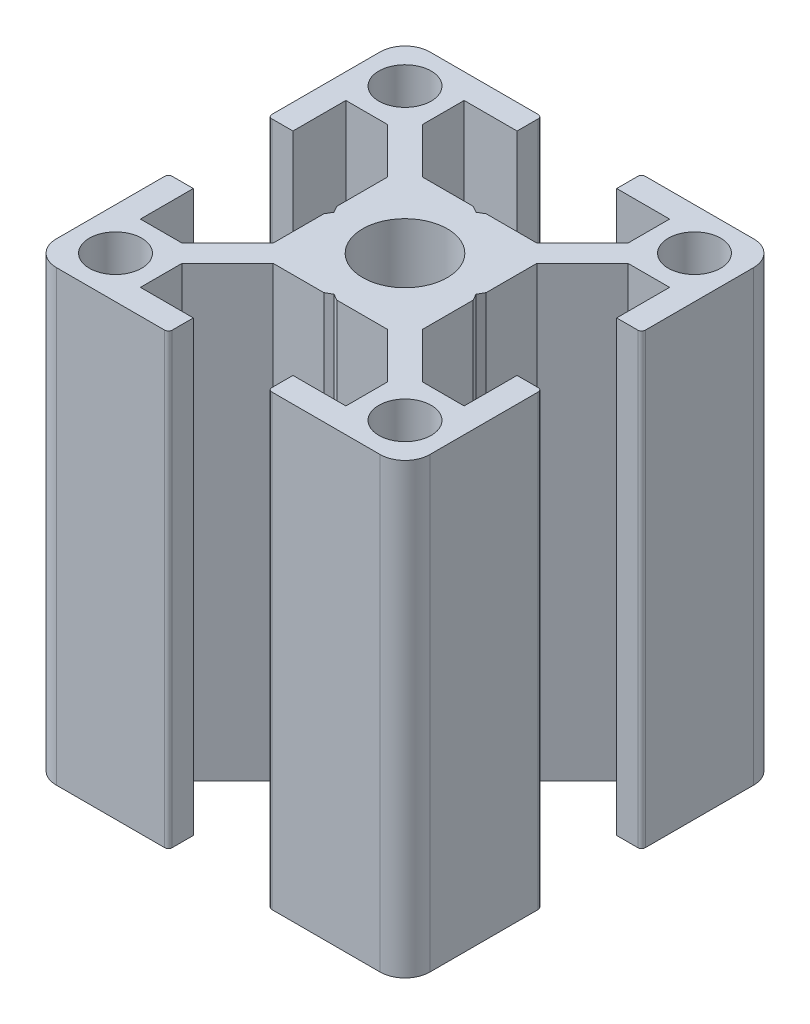
SolidWorks part; units mm, degrees
ref_plane "Front Plane" through (0, 0, 0) normal (0, 0, 1) x (1, 0, 0)
ref_plane "Top Plane" through (0, 0, 0) normal (0, 1, 0) x (1, 0, 0)
ref_plane "Right Plane" through (0, 0, 0) normal (1, 0, 0) x (0, 0, -1)
sketch "Sketch1" plane through (0, 0, 0) normal (0, 0, 1) x (1, 0, 0)
  line L0 (0, 0) -> (0, 36)
  dimension "D1" = 36
ref_plane "Plane1" through (0, 0, 0) normal (0, 1, 0) x (-1, 0, 0)
ref_plane "Plane2" through (0, 0, 0) normal (0, 1, 0) x (-1, 0, 0)
ref_plane "Plane3" through (0, 0, 0) normal (0, 1, 0) x (-1, 0, 0)
ref_plane "Plane4" through (0, 0, 0) normal (0, 1, 0) x (-1, 0, 0)
ref_plane "Plane6" through (0, 0, 0) normal (0, 1, 0) x (-1, 0, 0)
ref_plane "Plane7" through (0, 0, 0) normal (0, 1, 0) x (-1, 0, 0)
other "Structural Member1"
ref_plane "Plane8" through (0, 0, 0) normal (0, 1, 0) x (-1, 0, 0)
sketch "Model" plane through (0, 0, 0) normal (0, 1, 0) x (-1, 0, 0)
  line L0 (-15, 13) -> (-15, 4.3)
  line L1 (-4.3, 15) -> (-13, 15)
  line L2 (-4, 13) -> (-4, 14.7)
  line L3 (-8.25, 13) -> (-4, 13)
  line L4 (-8.25, 9.6642) -> (-8.25, 13)
  line L5 (-4.5858, 6) -> (-8.25, 9.6642)
  line L6 (-0.5196, 6) -> (-4.5858, 6)
  line L7 (0, 5.7) -> (-0.5196, 6)
  line L8 (0.5196, 6) -> (0, 5.7)
  line L9 (4.5858, 6) -> (0.5196, 6)
  line L10 (8.25, 9.6642) -> (4.5858, 6)
  line L11 (8.25, 13) -> (8.25, 9.6642)
  line L12 (4, 13) -> (8.25, 13)
  line L13 (4, 14.7) -> (4, 13)
  line L14 (13, 15) -> (4.3, 15)
  line L15 (15, 4.3) -> (15, 13)
  line L16 (13, 4) -> (14.7, 4)
  line L17 (13, 8.25) -> (13, 4)
  line L18 (9.6642, 8.25) -> (13, 8.25)
  line L19 (6, 4.5858) -> (9.6642, 8.25)
  line L20 (6, 0.5196) -> (6, 4.5858)
  line L21 (5.7, 0) -> (6, 0.5196)
  line L22 (6, -0.5196) -> (5.7, 0)
  line L23 (6, -4.5858) -> (6, -0.5196)
  line L24 (9.6642, -8.25) -> (6, -4.5858)
  line L25 (13, -8.25) -> (9.6642, -8.25)
  line L26 (13, -4) -> (13, -8.25)
  line L27 (14.7, -4) -> (13, -4)
  line L28 (15, -13) -> (15, -4.3)
  line L29 (4.3, -15) -> (13, -15)
  line L30 (4, -13) -> (4, -14.7)
  line L31 (8.25, -13) -> (4, -13)
  line L32 (8.25, -9.6642) -> (8.25, -13)
  line L33 (4.5858, -6) -> (8.25, -9.6642)
  line L34 (0.5196, -6) -> (4.5858, -6)
  line L35 (0, -5.7) -> (0.5196, -6)
  line L36 (-0.5196, -6) -> (0, -5.7)
  line L37 (-4.5858, -6) -> (-0.5196, -6)
  line L38 (-8.25, -9.6642) -> (-4.5858, -6)
  line L39 (-8.25, -13) -> (-8.25, -9.6642)
  line L40 (-4, -13) -> (-8.25, -13)
  line L41 (-4, -14.7) -> (-4, -13)
  line L42 (-13, -15) -> (-4.3, -15)
  line L43 (-15, -4.3) -> (-15, -13)
  line L44 (-13, -4) -> (-14.7, -4)
  line L45 (-13, -8.25) -> (-13, -4)
  line L46 (-9.6642, -8.25) -> (-13, -8.25)
  line L47 (-6, -4.5858) -> (-9.6642, -8.25)
  line L48 (-6, -0.5196) -> (-6, -4.5858)
  line L49 (-5.7, 0) -> (-6, -0.5196)
  line L50 (-6, 0.5196) -> (-5.7, 0)
  line L51 (-6, 4.5858) -> (-6, 0.5196)
  line L52 (-9.6642, 8.25) -> (-6, 4.5858)
  line L53 (-13, 8.25) -> (-9.6642, 8.25)
  line L54 (-13, 4) -> (-13, 8.25)
  line L55 (-14.7, 4) -> (-13, 4)
  arc A0 (-13, 15) -> (-15, 13) centre (-13, 13) ccw
  arc A1 (-4, 14.7) -> (-4.3, 15) centre (-4.3, 14.7) ccw
  arc A2 (4.3, 15) -> (4, 14.7) centre (4.3, 14.7) ccw
  arc A3 (15, 13) -> (13, 15) centre (13, 13) ccw
  arc A4 (14.7, 4) -> (15, 4.3) centre (14.7, 4.3) ccw
  arc A5 (15, -4.3) -> (14.7, -4) centre (14.7, -4.3) ccw
  arc A6 (13, -15) -> (15, -13) centre (13, -13) ccw
  arc A7 (4, -14.7) -> (4.3, -15) centre (4.3, -14.7) ccw
  arc A8 (-4.3, -15) -> (-4, -14.7) centre (-4.3, -14.7) ccw
  arc A9 (-15, -13) -> (-13, -15) centre (-13, -13) ccw
  arc A10 (-14.7, -4) -> (-15, -4.3) centre (-14.7, -4.3) ccw
  arc A11 (-15, 4.3) -> (-14.7, 4) centre (-14.7, 4.3) ccw
  circle A12 centre (11.625, -11.625) radius 2.1
  circle A13 centre (11.625, 11.625) radius 2.1
  circle A14 centre (0, 0) radius 3.4
  circle A15 centre (-11.625, -11.625) radius 2.1
  circle A16 centre (-11.625, 11.625) radius 2.1
  point P90 (0, 0)
  point P91 (-15, 15)
  point P92 (15, 15)
  point P93 (15, -15)
  point P94 (-15, -15)
  point P95 (0, 0)
